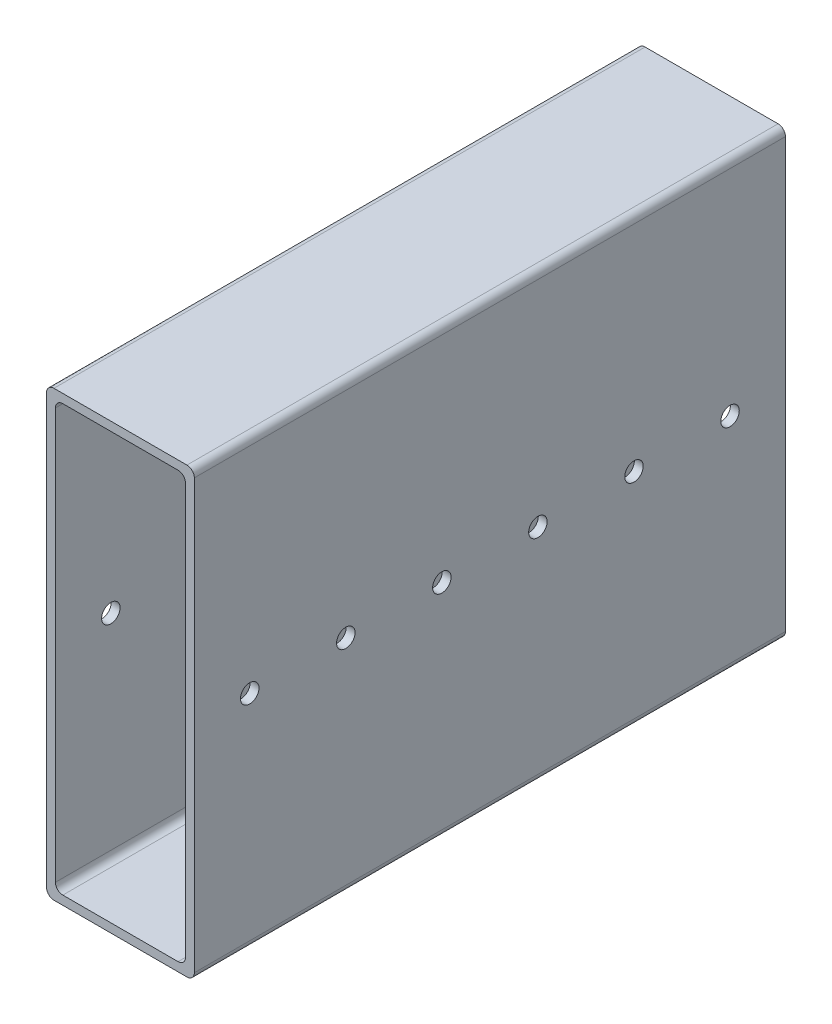
SolidWorks part; units mm, degrees
ref_plane "Front Plane" through (0, 0, 0) normal (0, 0, 1) x (1, 0, 0)
ref_plane "Top Plane" through (0, 0, 0) normal (0, 1, 0) x (1, 0, 0)
ref_plane "Right Plane" through (0, 0, 0) normal (1, 0, 0) x (0, 0, -1)
sketch "Sketch1" plane through (0, 0, 0) normal (0, 0, 1) x (1, 0, 0)
  line L1 (-11.3006, 134.8091) -> (34.4194, 134.8091)
  line L2 (-13.8406, 132.2691) -> (-13.8406, -15.0509)
  line L3 (-11.3006, -17.5909) -> (34.4194, -17.5909)
  line L4 (36.9594, 132.2691) -> (36.9594, -15.0509)
  arc A0 (34.4194, -17.5909) -> (36.9594, -15.0509) centre (34.4194, -15.0509) ccw
  arc A1 (-11.3006, -17.5909) -> (-13.8406, -15.0509) centre (-11.3006, -15.0509) cw
  arc A2 (36.9594, 132.2691) -> (34.4194, 134.8091) centre (34.4194, 132.2691) ccw
  arc A3 (-13.8406, 132.2691) -> (-11.3006, 134.8091) centre (-11.3006, 132.2691) cw
  dimension "D3" = 2.54
  dimension "D1" = 50.8
  dimension "D2" = 152.4
extrude "Boss-Extrude1" add sketch "Sketch1" along normal blind 203.2
shell "Shell1" thickness 3.048
fillet "Fillet1" radius 2.54 4 edges at (33.9114, -14.5429, 101.6) (-10.7926, -14.5429, 101.6) (33.9114, 131.7611, 101.6) (-10.7926, 131.7611, 101.6)
sketch "Sketch2" plane through (36.9594, 0, 0) normal (1, 0, 0) x (0, 0, -1)
  line L0 (-203.2, 58.6091) -> (0, 58.6091) construction
  line L1 (-203.2, -15.0509) -> (-203.2, 132.2691) construction
  line L2 (0, -15.0509) -> (0, 132.2691) construction
  line L3 (-184.15, 58.6091) -> (-19.05, 58.6091) construction
  circle A0 centre (-52.07, 58.6091) radius 3.175
  circle A1 centre (-85.09, 58.6091) radius 3.175
  circle A2 centre (-118.11, 58.6091) radius 3.175
  circle A3 centre (-151.13, 58.6091) radius 3.175
  circle A4 centre (-184.15, 58.6091) radius 3.175
  circle A5 centre (-19.05, 58.6091) radius 3.175
  point P18 (-101.6, 58.6091)
  point P19 (-101.6, 58.6091)
  dimension "D1" = 6.35
  dimension "D2" = 6
extrude "Cut-Extrude1" cut sketch "Sketch2" against normal blind 203.2
sketch "Sketch3" plane through (0, 0, 203.2) normal (0, 0, 1) x (1, 0, 0)
  line L0 (-13.8406, 58.6091) -> (36.9594, 58.6091) construction
  line L1 (-13.8406, 132.2691) -> (-13.8406, -15.0509) construction
  line L2 (36.9594, -15.0509) -> (36.9594, 132.2691) construction
  line L3 (11.5594, 134.8091) -> (11.5594, -17.5909) construction
  line L4 (34.4194, 134.8091) -> (-11.3006, 134.8091) construction
  line L5 (-11.3006, -17.5909) -> (34.4194, -17.5909) construction
  circle A0 centre (11.5594, 58.6091) radius 7.0257
  point P12 (11.5594, 58.6091)
